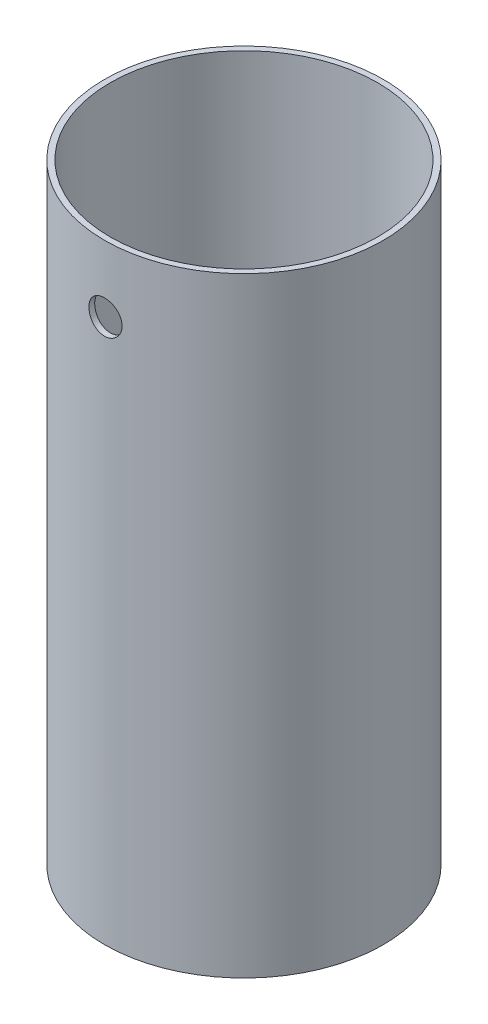
SolidWorks part; units mm, degrees
material "PVC Rígido"
ref_plane "Alzado" through (0, 0, 0) normal (0, 0, 1) x (1, 0, 0)
ref_plane "Planta" through (0, 0, 0) normal (0, 1, 0) x (1, 0, 0)
ref_plane "Vista lateral" through (0, 0, 0) normal (1, 0, 0) x (0, 0, -1)
sketch "Croquis2" plane through (0, 0, 0) normal (0, 1, 0) x (1, 0, 0)
  circle A0 centre (0, 0) radius 76.7
  circle A1 centre (0, 0) radius 80
  dimension "D1" = 160
  dimension "D2" = 3.3
extrude "Saliente-Extruir1" add sketch "Croquis2" against normal blind 350
sketch "Croquis3" plane through (0, 0, 0) normal (0, 0, 1) x (1, 0, 0)
  line L0 (0, 0) -> (0, -76.2) construction
  line L6 (80, 0) -> (-80, 0) construction
  circle A0 centre (0, -38.1) radius 9.525
  dimension "D2" = 19.05
  dimension "D1" = 38.1
extrude "Cortar-Extruir1" cut sketch "Croquis3" along normal through all
